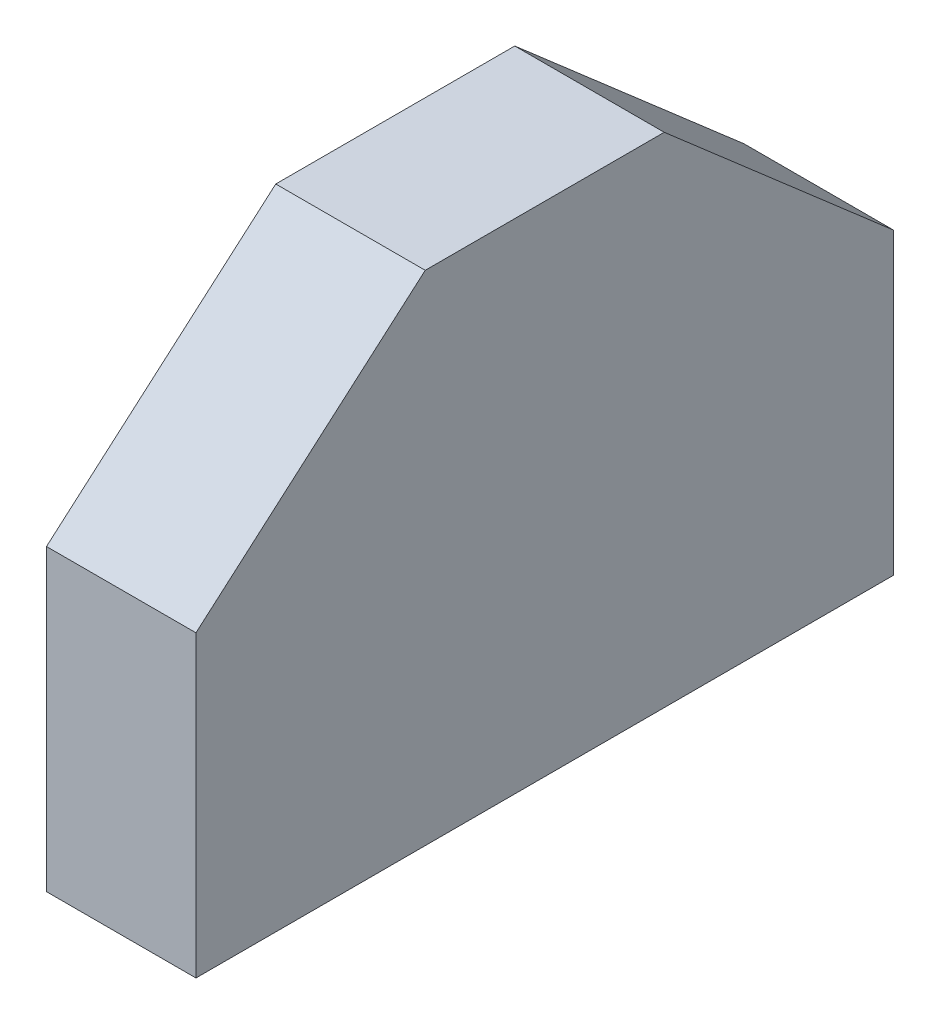
SolidWorks part; units mm, degrees
ref_plane "Front Plane" through (0, 0, 0) normal (0, 0, 1) x (1, 0, 0)
ref_plane "Top Plane" through (0, 0, 0) normal (0, 1, 0) x (1, 0, 0)
ref_plane "Right Plane" through (0, 0, 0) normal (1, 0, 0) x (0, 0, -1)
sketch "Esquisse1" plane through (0, 0, 0) normal (0, 1, 0) x (1, 0, 0)
  line L1 (7.5, -35) -> (-7.5, -35)
  line L2 (7.5, -35) -> (7.5, 35)
  line L3 (7.5, 35) -> (-7.5, 35)
  line L4 (-7.5, -35) -> (-7.5, 35)
  line L5 (7.5, -35) -> (-7.5, 35) construction
  line L6 (7.5, 35) -> (-7.5, -35) construction
  point P0 (0, 0)
  dimension "70" = 70
  dimension "D2" = 15
extrude "Boss.-Extru.1" add sketch "Esquisse1" along normal blind 50
chamfer "Chanfrein1" distance 20 angle 49 2 edges at (0, 50, -35) (0, 50, 35)
sketch "Esquisse2" plane through (0, 0, 0) normal (0, -1, 0) x (1, 0, 0)
  line L8 (-4.5, 32) -> (-4.5, -32)
  line L9 (-4.5, -32) -> (4.5, -32)
  line L10 (4.5, -32) -> (4.5, 32)
  line L11 (4.5, 32) -> (-4.5, 32)
  line L12 (-4.5, 32) -> (-4.5, -32)
  line L13 (-4.5, -32) -> (4.5, -32)
  line L14 (4.5, -32) -> (4.5, 32)
  line L15 (4.5, 32) -> (-4.5, 32)
  dimension "D1" = 3
extrude "Enlèv. mat.-Extru.1" cut sketch "Esquisse2" against normal up to vertex (30 mm away)
